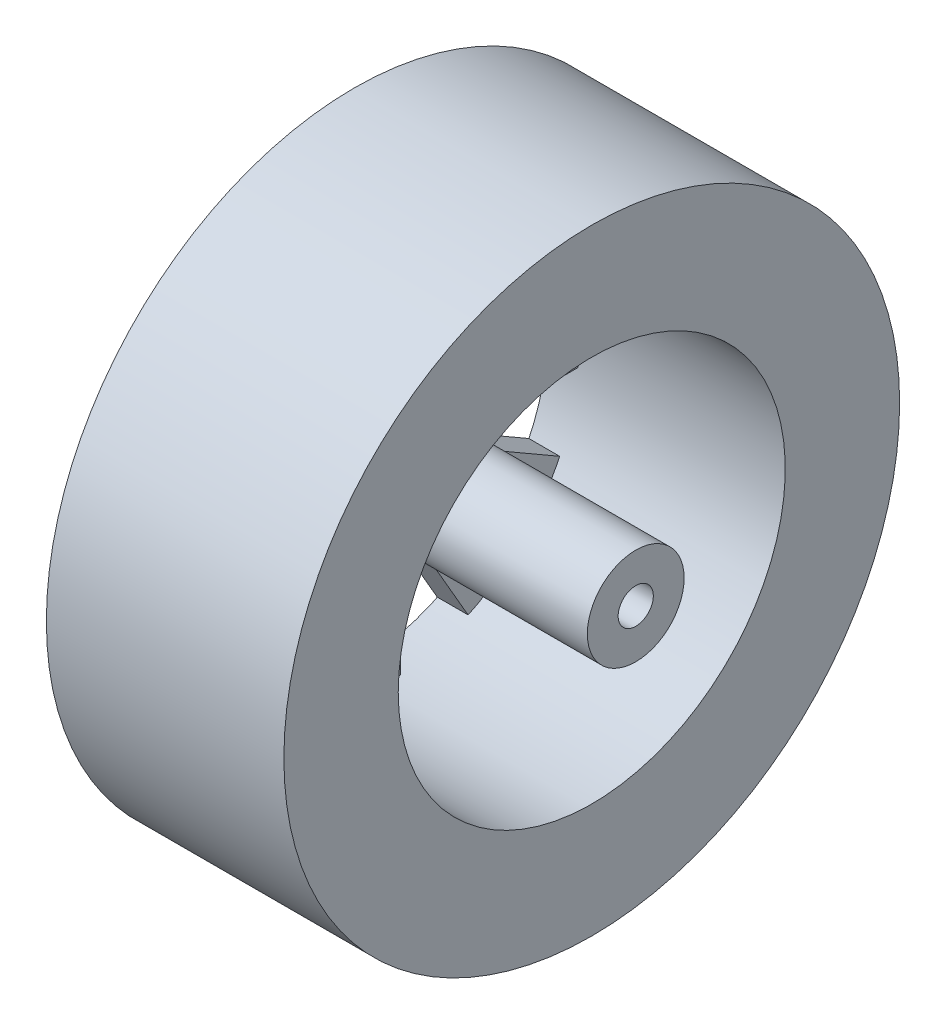
SolidWorks part; units mm, degrees
ref_plane "Alzado" through (0, 0, 0) normal (0, 0, 1) x (1, 0, 0)
ref_plane "Planta" through (0, 0, 0) normal (0, 1, 0) x (1, 0, 0)
ref_plane "Vista lateral" through (0, 0, 0) normal (1, 0, 0) x (0, 0, -1)
sketch "Sketch1" plane through (0, 0, 0) normal (0, 0, 1) x (1, 0, 0)
  line L0 (0, 0) -> (27, 0) construction
  line L1 (0, 35) -> (27, 35)
  line L2 (27, 35) -> (27, 22)
  line L3 (27, 22) -> (0, 22)
  line L4 (0, 22) -> (0, 35)
  line L5 (0, 2) -> (0, 5.5)
  line L6 (0, 5.5) -> (27, 5.5)
  line L7 (27, 5.5) -> (27, 2)
  line L9 (0, 2) -> (27, 2)
  dimension "D1" = 35
  dimension "D2" = 13
  dimension "D3" = 5.5
  dimension "D4" = 27
  dimension "D5" = 2
revolve "Revolve2" add sketch "Sketch1" angle 360 about L0
sketch "Sketch3" plane through (27, 0, 0) normal (1, 0, 0) x (0, 0, -1)
  circle A0 centre (0, 0) radius 2 construction
  circle A1 centre (0, 0) radius 5.5
  circle A2 centre (0, 0) radius 5.5
  circle A3 centre (0, 0) radius 2
  dimension "D1" = 0
extrude "Boss-Extrude1" add sketch "Sketch3" along normal blind 5
sketch "Sketch4" plane through (0, 0, 0) normal (-1, 0, 0) x (0, 0, 1)
  circle A0 centre (0, 0) radius 8.75
  dimension "D1" = 17.5
extrude "Boss-Extrude2" add sketch "Sketch4" against normal blind 3.5
sketch "Sketch5" plane through (0, 0, 0) normal (-1, 0, 0) x (0, 0, 1)
  line L0 (-35, 0) -> (35, 0) construction
  line L1 (-1.75, 8.5732) -> (-1.75, 21.9303)
  line L2 (1.75, 8.5732) -> (1.75, 21.9303)
  line L3 (-35, 0) -> (35, 0) construction
  line L38 (2.7711, 8.2996) -> (9.4496, 19.8672)
  line L39 (5.8022, 6.5496) -> (12.4807, 18.1172)
  line L40 (6.5496, 5.8022) -> (18.1172, 12.4807)
  line L41 (8.2996, 2.7711) -> (19.8672, 9.4496)
  line L42 (8.5732, 1.75) -> (21.9303, 1.75)
  line L43 (8.5732, -1.75) -> (21.9303, -1.75)
  line L44 (8.2996, -2.7711) -> (19.8672, -9.4496)
  line L45 (6.5496, -5.8022) -> (18.1172, -12.4807)
  line L46 (5.8022, -6.5496) -> (12.4807, -18.1172)
  line L47 (2.7711, -8.2996) -> (9.4496, -19.8672)
  line L48 (1.75, -8.5732) -> (1.75, -21.9303)
  line L49 (-1.75, -8.5732) -> (-1.75, -21.9303)
  line L50 (-2.7711, -8.2996) -> (-9.4496, -19.8672)
  line L51 (-5.8022, -6.5496) -> (-12.4807, -18.1172)
  line L52 (-6.5496, -5.8022) -> (-18.1172, -12.4807)
  line L53 (-8.2996, -2.7711) -> (-19.8672, -9.4496)
  line L54 (-8.5732, -1.75) -> (-21.9303, -1.75)
  line L55 (-8.5732, 1.75) -> (-21.9303, 1.75)
  line L56 (-8.2996, 2.7711) -> (-19.8672, 9.4496)
  line L57 (-6.5496, 5.8022) -> (-18.1172, 12.4807)
  line L58 (-5.8022, 6.5496) -> (-12.4807, 18.1172)
  line L59 (-2.7711, 8.2996) -> (-9.4496, 19.8672)
  circle A0 centre (0, 0) radius 35 construction
  circle A1 centre (0, 0) radius 22 construction
  arc A3 (1.75, 21.9303) -> (-1.75, 21.9303) centre (0, 0) ccw
  arc A19 (1.75, 8.5732) -> (-1.75, 8.5732) centre (0, 0) ccw
  circle A20 centre (0, 0) radius 8.75 construction
  arc A21 (12.4807, 18.1172) -> (9.4496, 19.8672) centre (0, 0) ccw
  arc A22 (5.8022, 6.5496) -> (2.7711, 8.2996) centre (0, 0) ccw
  arc A23 (19.8672, 9.4496) -> (18.1172, 12.4807) centre (0, 0) ccw
  arc A24 (8.2996, 2.7711) -> (6.5496, 5.8022) centre (0, 0) ccw
  arc A25 (21.9303, -1.75) -> (21.9303, 1.75) centre (0, 0) ccw
  arc A26 (8.5732, -1.75) -> (8.5732, 1.75) centre (0, 0) ccw
  arc A27 (18.1172, -12.4807) -> (19.8672, -9.4496) centre (0, 0) ccw
  arc A28 (6.5496, -5.8022) -> (8.2996, -2.7711) centre (0, 0) ccw
  arc A29 (9.4496, -19.8672) -> (12.4807, -18.1172) centre (0, 0) ccw
  arc A30 (2.7711, -8.2996) -> (5.8022, -6.5496) centre (0, 0) ccw
  arc A31 (-1.75, -21.9303) -> (1.75, -21.9303) centre (0, 0) ccw
  arc A32 (-1.75, -8.5732) -> (1.75, -8.5732) centre (0, 0) ccw
  arc A33 (-12.4807, -18.1172) -> (-9.4496, -19.8672) centre (0, 0) ccw
  arc A34 (-5.8022, -6.5496) -> (-2.7711, -8.2996) centre (0, 0) ccw
  arc A35 (-19.8672, -9.4496) -> (-18.1172, -12.4807) centre (0, 0) ccw
  arc A36 (-8.2996, -2.7711) -> (-6.5496, -5.8022) centre (0, 0) ccw
  arc A37 (-21.9303, 1.75) -> (-21.9303, -1.75) centre (0, 0) ccw
  arc A38 (-8.5732, 1.75) -> (-8.5732, -1.75) centre (0, 0) ccw
  arc A39 (-18.1172, 12.4807) -> (-19.8672, 9.4496) centre (0, 0) ccw
  arc A40 (-6.5496, 5.8022) -> (-8.2996, 2.7711) centre (0, 0) ccw
  arc A41 (-9.4496, 19.8672) -> (-12.4807, 18.1172) centre (0, 0) ccw
  arc A42 (-2.7711, 8.2996) -> (-5.8022, 6.5496) centre (0, 0) ccw
  point P13 (0, 0)
  point P22 (0, 8.75)
  point P66 (0, 0)
  dimension "D2" = 12
  dimension "D1" = 3.5
extrude "Boss-Extrude3" add sketch "Sketch5" against normal blind 3.5 separate body
